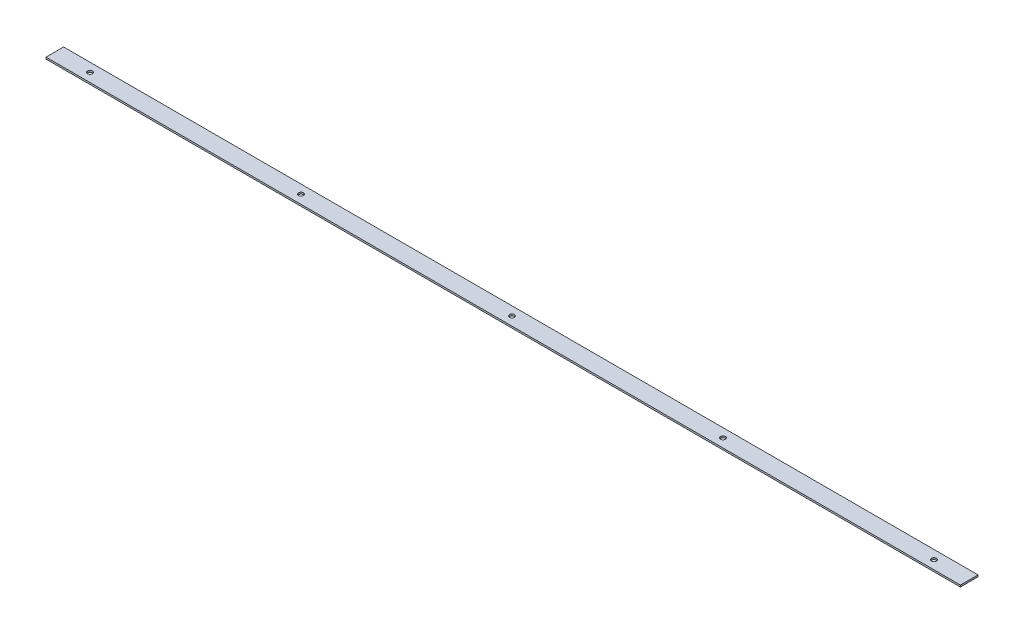
SolidWorks part; units mm, degrees
ref_plane "Front Plane" through (0, 0, 0) normal (0, 0, 1) x (1, 0, 0)
ref_plane "Top Plane" through (0, 0, 0) normal (0, 1, 0) x (1, 0, 0)
ref_plane "Right Plane" through (0, 0, 0) normal (1, 0, 0) x (0, 0, -1)
sketch "Sketch1" plane through (0, 0, 0) normal (0, 1, 0) x (1, 0, 0)
  line L1 (-650, -12.5) -> (650, -12.5)
  line L2 (-650, -12.5) -> (-650, 12.5)
  line L3 (-650, 12.5) -> (650, 12.5)
  line L4 (650, -12.5) -> (650, 12.5)
  line L5 (-650, -12.5) -> (650, 12.5) construction
  line L6 (-650, 12.5) -> (650, -12.5) construction
  point P0 (0, 0)
  dimension "D1" = 25
  dimension "D2" = 1300
extrude "Boss-Extrude1" add sketch "Sketch1" along normal blind 2.5
sketch "Sketch2" plane through (0, 2.5, 0) normal (0, 1, 0) x (1, 0, 0)
  line L0 (-650, 12.5) -> (-650, -12.5) construction
  circle A0 centre (-600, 0) radius 3.5
  dimension "D1" = 7
  dimension "D2" = 50
extrude "Cut-Extrude1" cut sketch "Sketch2" against normal through all both and the other way through all
pattern_linear "LPattern1" count 5 spacing 300 along (1, 0, 0) of "Cut-Extrude1"
